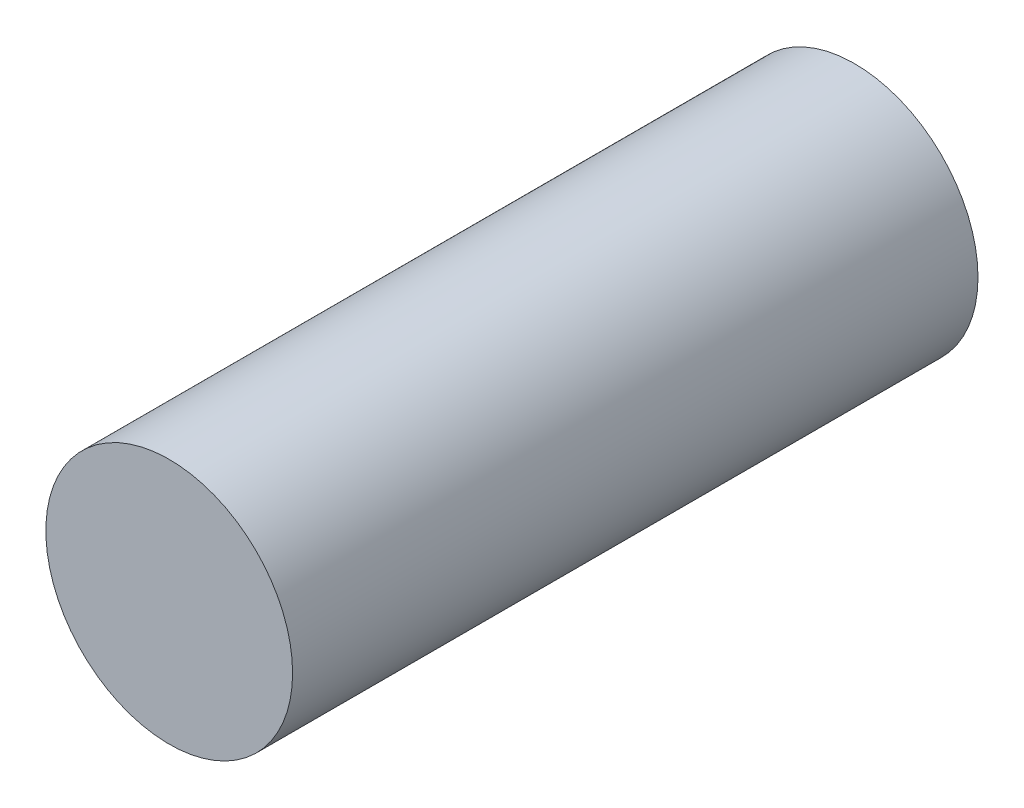
SolidWorks part; units mm, degrees
ref_plane "Front Plane" through (0, 0, 0) normal (0, 0, 1) x (1, 0, 0)
ref_plane "Top Plane" through (0, 0, 0) normal (0, 1, 0) x (1, 0, 0)
ref_plane "Right Plane" through (0, 0, 0) normal (1, 0, 0) x (0, 0, -1)
sketch "Sketch1" plane through (0, 0, 0) normal (0, 0, 1) x (1, 0, 0)
  circle A0 centre (0, 0) radius 2.286
  dimension ".18in" = 4.572
extrude "Boss-Extrude1" add sketch "Sketch1" along normal blind 12.7
